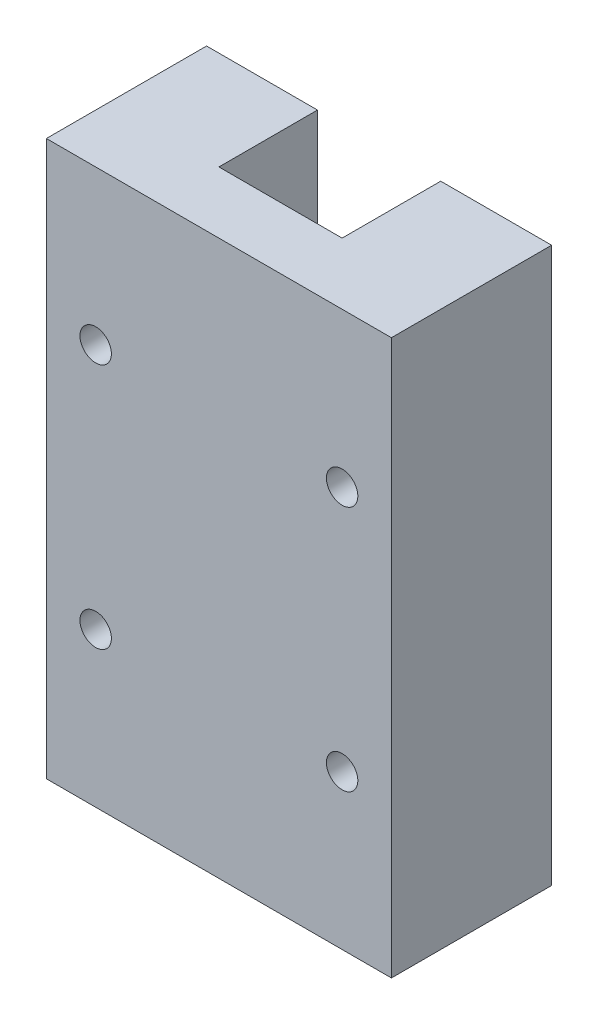
SolidWorks part; units mm, degrees
ref_plane "Front Plane" through (0, 0, 0) normal (0, 0, 1) x (1, 0, 0)
ref_plane "Top Plane" through (0, 0, 0) normal (0, 1, 0) x (1, 0, 0)
ref_plane "Right Plane" through (0, 0, 0) normal (1, 0, 0) x (0, 0, -1)
sketch "Sketch1" plane through (0, 0, 0) normal (0, 1, 0) x (1, 0, 0)
  line L0 (0, -7.15) -> (0, 7.15) construction
  line L1 (-14, 13) -> (14, 13)
  line L2 (-14, 13) -> (-14, 0)
  line L3 (-14, 0) -> (14, 0)
  line L4 (14, 13) -> (14, 0)
  line L5 (-14, 13) -> (14, 0) construction
  line L6 (-14, 0) -> (14, 13) construction
  line L7 (-15.4, 0) -> (15.4, 0) construction
  line L9 (-5, 21) -> (5, 21)
  line L10 (-5, 21) -> (-5, 5)
  line L11 (-5, 5) -> (5, 5)
  line L12 (5, 21) -> (5, 5)
  line L13 (-5, 21) -> (5, 5) construction
  line L14 (-5, 5) -> (5, 21) construction
  point P0 (0, 6.5)
  point P9 (0, 13)
  dimension "D1" = 28
  dimension "D2" = 10
  dimension "D3" = 8
  dimension "D4" = 13
extrude "Boss-Extrude1" add sketch "Sketch1" along normal blind 45 contours L1 L12 L11 L10 L2 L3 L4
sketch "Sketch2" plane through (0, 0, 0) normal (0, 0, 1) x (1, 0, 0)
  line L0 (0, -7.15) -> (0, 7.15) construction
  line L1 (-10, 12.5) -> (10, 12.5) construction
  line L2 (-10, 12.5) -> (-10, 32.5) construction
  line L3 (-10, 32.5) -> (10, 32.5) construction
  line L4 (10, 12.5) -> (10, 32.5) construction
  line L5 (-10, 12.5) -> (10, 32.5) construction
  line L6 (-10, 32.5) -> (10, 12.5) construction
  line L7 (14, 45) -> (14, 0) construction
  circle A0 centre (-10, 32.5) radius 1.2741
  circle A1 centre (10, 32.5) radius 1.2741
  circle A2 centre (10, 12.5) radius 1.2741
  circle A3 centre (-10, 12.5) radius 1.2741
  point P0 (0, 22.5)
  point P10 (14, 22.5)
  dimension "D1" = 20
extrude "Cut-Extrude1" cut sketch "Sketch2" against normal up to next
